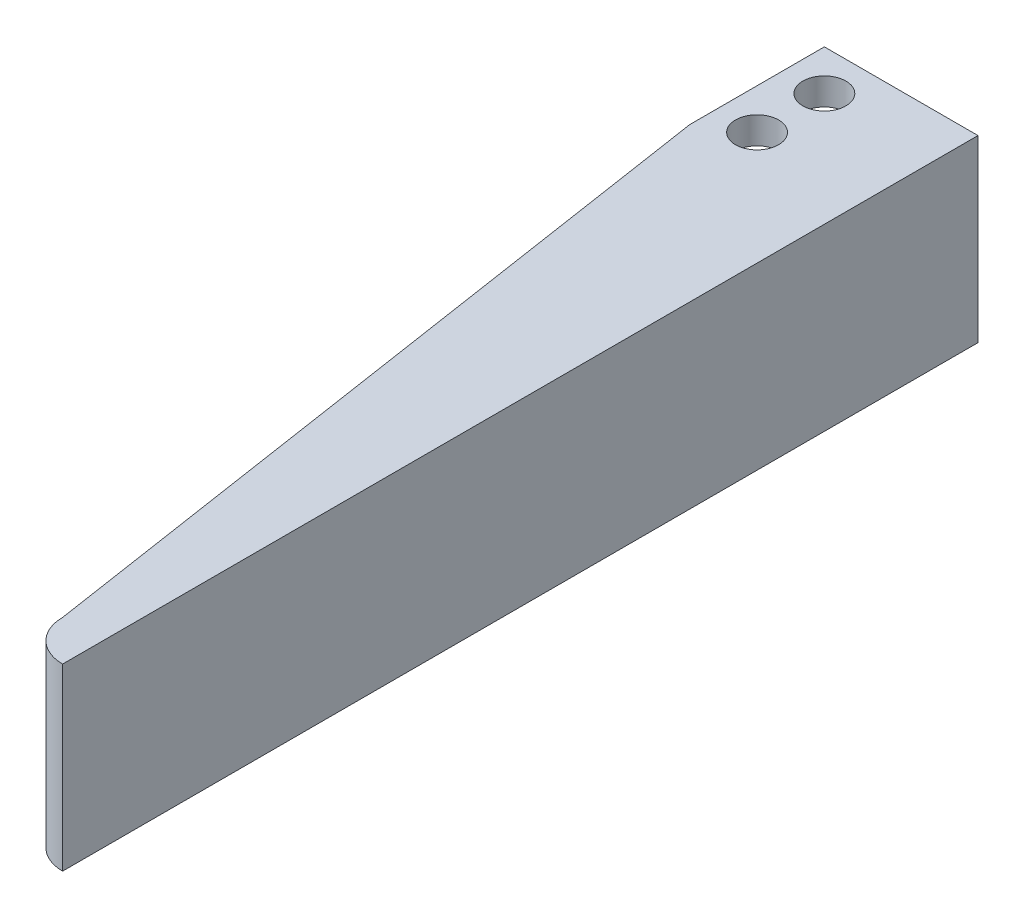
SolidWorks part; units mm, degrees
ref_plane "Front Plane" through (0, 0, 0) normal (0, 0, 1) x (1, 0, 0)
ref_plane "Top Plane" through (0, 0, 0) normal (0, 1, 0) x (1, 0, 0)
ref_plane "Right Plane" through (0, 0, 0) normal (1, 0, 0) x (0, 0, -1)
sketch "Sketch1" plane through (0, 0, 0) normal (0, 1, 0) x (1, 0, 0)
  line L0 (-5.7062, 0) -> (5.7062, 0)
  line L1 (-5.7062, 0) -> (-5.7062, -10)
  line L2 (-5.7062, -10) -> (2.7063, -65)
  line L5 (5.7062, 0) -> (5.7063, -65) construction
  line L6 (5.7063, -68) -> (5.7062, 0)
  arc A0 (2.7063, -65) -> (5.7063, -68) centre (5.7063, -65) ccw
  circle A1 centre (-2.7062, -3) radius 1.6
  circle A2 centre (-2.7062, -8) radius 1.6
  point P1 (0, 0)
  point P3 (0, 0)
  dimension "D1" = 3
  dimension "D8" = 3.2
  dimension "D2" = 11.4125
  dimension "D3" = 10
  dimension "D4" = 55
  dimension "D5" = 3
  dimension "D6" = 5
  dimension "D7" = 3
extrude "Boss-Extrude1" add sketch "Sketch1" along normal blind 2
sketch "Sketch2" plane through (0, 0, 0) normal (0, -1, 0) x (1, 0, 0)
  line L0 (5.7062, 0) -> (-5.7062, 0) construction
  line L1 (5.7063, 68) -> (5.7063, 0)
  line L8 (5.7063, 0) -> (2.7063, 0)
  line L9 (2.7063, 65) -> (2.7063, 0)
  line L10 (5.7063, 68) -> (5.7062, 0) construction
  arc A2 (5.7063, 68) -> (2.7063, 65) centre (5.7063, 65) ccw
extrude "Boss-Extrude2" add sketch "Sketch2" along normal blind 4.6625
ref_plane "Plane1" through (0, -4.6625, 0) normal (0, -1, 0) x (-1, 0, 0)
mirror "Mirror6" about plane through (0, -4.6625, 0) normal (0, -1, 0) of "Boss-Extrude1", "Boss-Extrude2"
mirror "Mirror7" about plane through (0, -4.6625, 0) normal (0, -1, 0) of "Boss-Extrude1"
